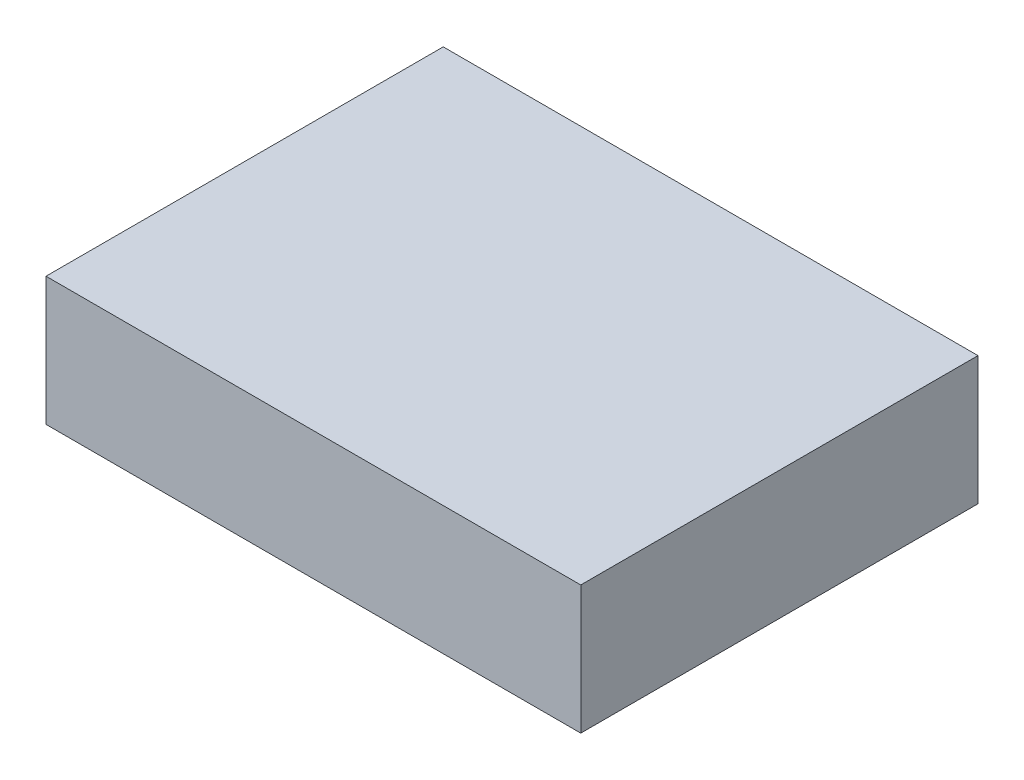
SolidWorks part; units mm, degrees
ref_plane "Front Plane" through (0, 0, 0) normal (0, 0, 1) x (1, 0, 0)
ref_plane "Top Plane" through (0, 0, 0) normal (0, 1, 0) x (1, 0, 0)
ref_plane "Right Plane" through (0, 0, 0) normal (1, 0, 0) x (0, 0, -1)
sketch "Sketch1" plane through (0, 0, 0) normal (0, 1, 0) x (1, 0, 0)
  line L1 (437.5, 0) -> (-437.5, 0)
  line L2 (437.5, 0) -> (437.5, 650)
  line L3 (437.5, 650) -> (-437.5, 650)
  line L4 (-437.5, 0) -> (-437.5, 650)
  dimension "D1" = 875
  dimension "D2" = 650
extrude "Boss-Extrude1" add sketch "Sketch1" against normal blind 210
